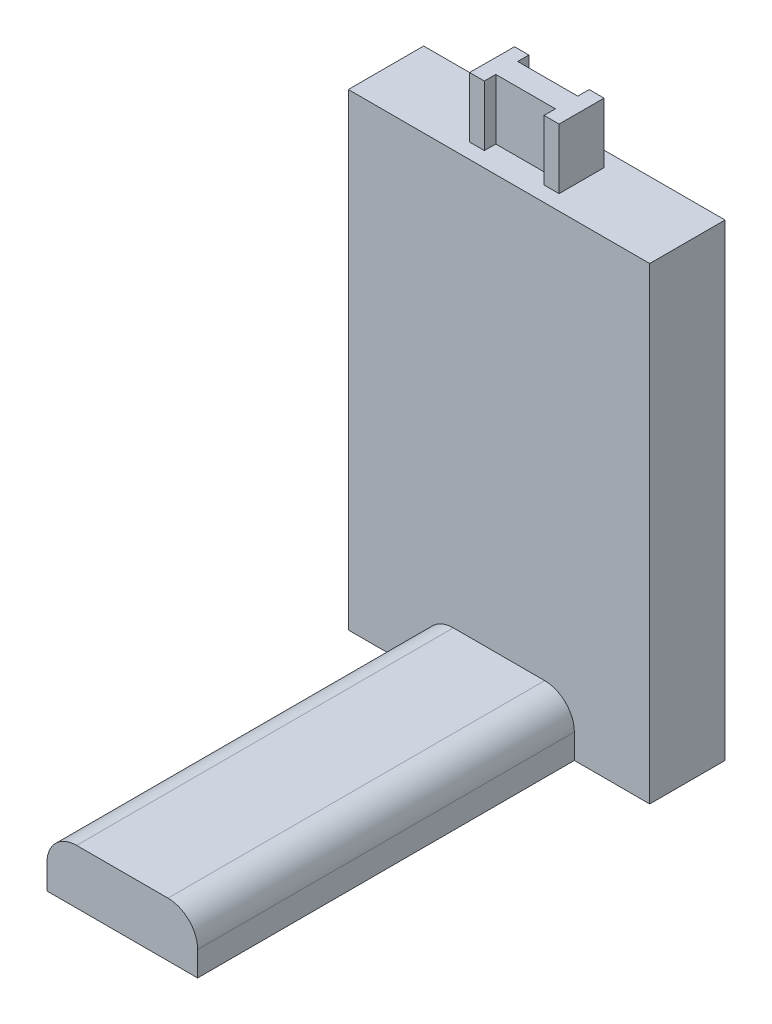
SolidWorks part; units mm, degrees
ref_plane "Front Plane" through (0, 0, 0) normal (0, 0, 1) x (1, 0, 0)
ref_plane "Top Plane" through (0, 0, 0) normal (0, 1, 0) x (1, 0, 0)
ref_plane "Right Plane" through (0, 0, 0) normal (1, 0, 0) x (0, 0, -1)
sketch "Sketch3" plane through (0, 0, 0) normal (0, 1, 0) x (1, 0, 0)
  line L0 (-25.4, 0) -> (76.2, 0)
  line L1 (-25.4, 0) -> (-25.4, 25.4)
  line L2 (-25.4, 25.4) -> (76.2, 25.4)
  line L3 (76.2, 25.4) -> (76.2, 0)
extrude "Boss-Extrude1" add sketch "Sketch3" along normal blind 157.8
sketch "Sketch6" plane through (0, 157.8, 0) normal (0, 1, 0) x (1, 0, 0)
  line L0 (25.4, 25.4) -> (25.4, 0) construction
  line L3 (76.2, 25.4) -> (-25.4, 25.4) construction
  line L4 (-25.4, 0) -> (76.2, 0) construction
  line L5 (25.4106, 25.4063) -> (25.4106, 0.0063) construction
  line L6 (25.4106, 12.7063) -> (35.4106, 12.7063) construction
  line L7 (25.4106, 12.7063) -> (15.4106, 12.7063) construction
  line L21 (10.4477, 20.1897) -> (15.2935, 20.1897)
  line L22 (15.2935, 20.1897) -> (15.2935, 16.4096)
  line L23 (15.2935, 16.4096) -> (35.527, 16.4096)
  line L24 (35.527, 16.4096) -> (35.527, 20.2636)
  line L25 (35.527, 20.2636) -> (40.5334, 20.2636)
  line L26 (40.5334, 20.2636) -> (40.5334, 5.1146)
  line L27 (40.5334, 5.1146) -> (35.4601, 5.1146)
  line L28 (35.4601, 5.1146) -> (35.4601, 8.9422)
  line L29 (35.4601, 8.9422) -> (15.3672, 8.9422)
  line L30 (15.3672, 8.9422) -> (15.3672, 5.0873)
  line L31 (15.3672, 5.0873) -> (10.3888, 5.0873)
  line L32 (10.3888, 5.0873) -> (10.4477, 20.1897)
extrude "Boss-Extrude4" add sketch "Sketch6" along normal blind 20.32
sketch "Sketch7" plane through (0, 0, 0) normal (0, -1, 0) x (-1, 0, 0)
  line L0 (-25.4, 12.7) -> (5.08, 12.7) construction
  line L2 (-25.4, 25.4) -> (-25.4, 12.7) construction
  line L3 (-25.4, 12.7) -> (-55.88, 12.7) construction
  line L4 (-76.2, 25.4) -> (25.4, 25.4) construction
  circle A1 centre (5.08, 12.7) radius 5.207
  circle A2 centre (-55.88, 12.7) radius 5.207
  dimension "D1" = 10.414
  dimension "D2" = 10.414
extrude "Cut-Extrude1" cut sketch "Sketch7" against normal blind 17.78
sketch "Sketch8" plane through (0, 0, 0) normal (0, 0, 1) x (1, 0, 0)
  line L0 (25.4, 0) -> (25.4, 18.3216) construction
  line L1 (-25.4, 0) -> (76.2, 0) construction
  line L2 (25.4, 18.3216) -> (50.8, 18.3216) construction
  line L3 (25.4, 18.3216) -> (0, 18.3216) construction
  line L5 (0, 18.3216) -> (50.8, 18.3216)
  line L6 (0, 18.3216) -> (0, 0)
  line L7 (0, 0) -> (50.8, 0)
  line L8 (50.8, 18.3216) -> (50.8, 0)
extrude "Boss-Extrude5" add sketch "Sketch8" along normal blind 127
fillet "Fillet1" radius 10 1 edges at (50.8, 18.3216, 63.5)
fillet "Fillet2" radius 10 1 edges at (0, 18.3216, 63.5)
